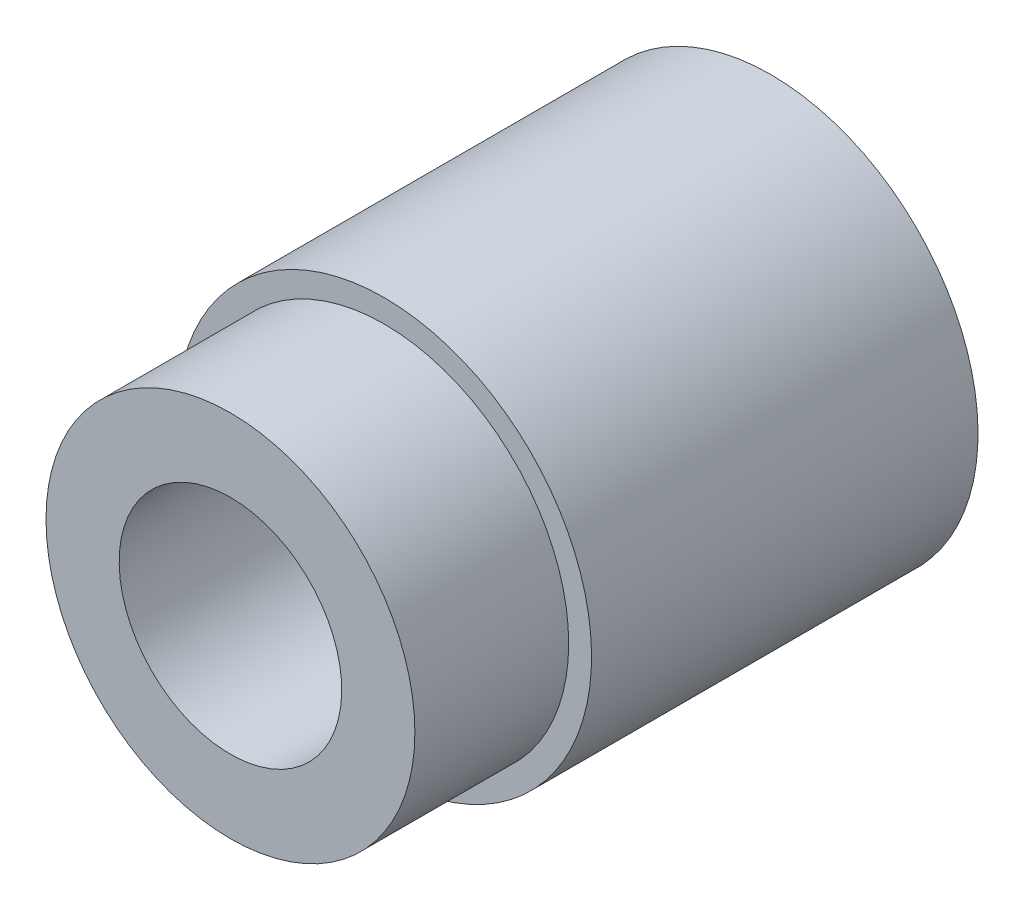
SolidWorks part; units mm, degrees
material "ABS"
ref_plane "Front" through (0, 0, 0) normal (0, 0, 1) x (1, 0, 0)
ref_plane "Top" through (0, 0, 0) normal (0, 1, 0) x (1, 0, 0)
ref_plane "Right" through (0, 0, 0) normal (1, 0, 0) x (0, 0, -1)
sketch "Sketch1" plane through (0, 0, 0) normal (1, 0, 0) x (0, 0, -1)
  line L0 (0, 0) -> (-17.5768, 0) construction
  line L1 (0, 3.6195) -> (-17.5768, 3.6195)
  line L2 (-17.5768, 3.6195) -> (-17.5768, 6)
  line L3 (-17.5768, 6) -> (-12.573, 6)
  line L4 (-12.573, 6) -> (-12.573, 6.7437)
  line L5 (-12.573, 6.7437) -> (0, 6.7437)
  line L6 (0, 6.7437) -> (0, 3.6195)
  dimension "D1" = 7.239
  dimension "D2" = 12
  dimension "D3" = 13.4874
  dimension "D4" = 5.0038
  dimension "D5" = 12.573
revolve "Revolve1" add sketch "Sketch1" angle 360 about L0
